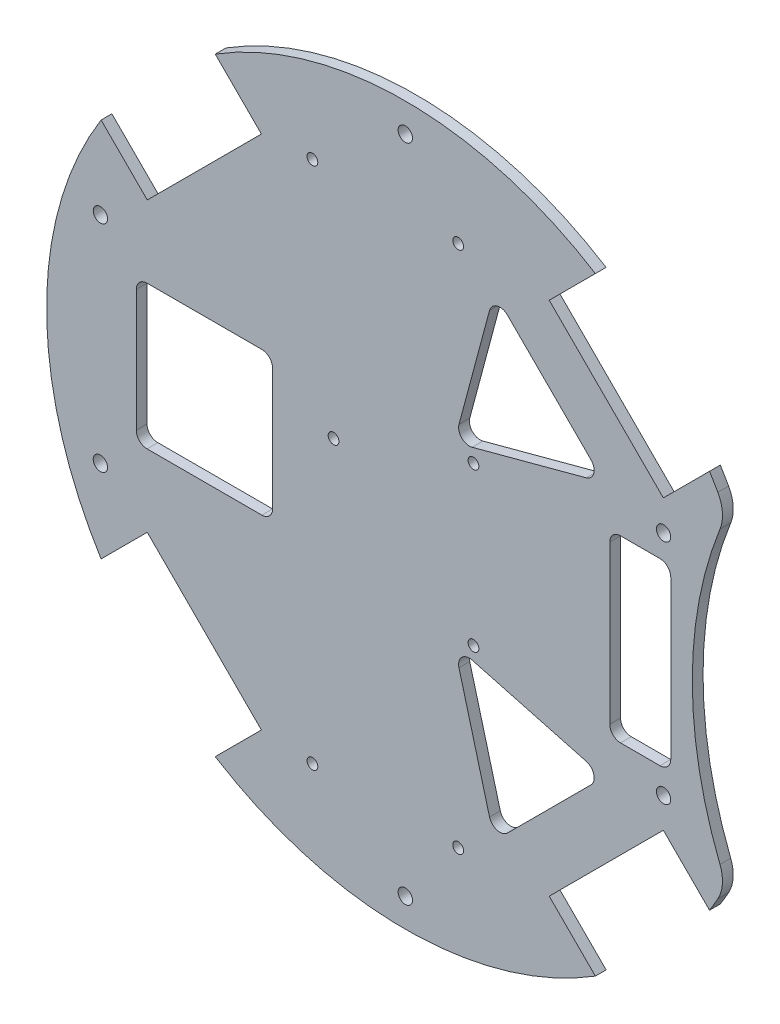
SolidWorks part; units mm, degrees
ref_plane "Alzado" through (0, 0, 0) normal (0, 0, 1) x (1, 0, 0)
ref_plane "Planta" through (0, 0, 0) normal (0, 1, 0) x (1, 0, 0)
ref_plane "Vista lateral" through (0, 0, 0) normal (1, 0, 0) x (0, 0, -1)
sketch "Croquis1" plane through (0, 0, 0) normal (0, 0, 1) x (1, 0, 0)
  circle A0 centre (0, 0) radius 100
  dimension "D1" = 200
extrude "Saliente-Extruir1" add sketch "Croquis1" along normal blind 3
sketch "Croquis3" plane through (0, 0, 3) normal (0, 0, 1) x (1, 0, 0)
  line L0 (0, 0) -> (190, 0) construction
  circle A0 centre (190, 0) radius 110
  dimension "D1" = 220
  dimension "D2" = 190
extrude "Cortar-Extruir1" cut sketch "Croquis3" against normal blind 3
fillet "Redondeo1" radius 10 2 edges at (89.4737, -44.6594, 1.5) (89.4737, 44.6594, 1.5)
sketch "Croquis7" plane through (0, 0, 3) normal (0, 0, 1) x (1, 0, 0)
  line L0 (-71.9393, -40.1195) -> (-40.1195, -71.9393)
  line L1 (-71.9393, -40.1195) -> (-89.617, -57.7972)
  line L2 (-40.1195, -71.9393) -> (-57.7972, -89.617)
  line L3 (-89.617, -57.7972) -> (-57.7972, -89.617)
  line L6 (0, -100) -> (0, 100) construction
  line L7 (-100, 0) -> (80, 0) construction
  line L8 (-40.1195, 71.9393) -> (-71.9393, 40.1195)
  line L9 (-40.1195, 71.9393) -> (-57.7972, 89.617)
  line L10 (-57.7972, 89.617) -> (-89.617, 57.7972)
  line L11 (-71.9393, 40.1195) -> (-89.617, 57.7972)
  line L12 (71.9393, 40.1195) -> (40.1195, 71.9393)
  line L13 (71.9393, 40.1195) -> (89.617, 57.7972)
  line L14 (89.617, 57.7972) -> (57.7972, 89.617)
  line L15 (40.1195, 71.9393) -> (57.7972, 89.617)
  line L16 (40.1195, -71.9393) -> (71.9393, -40.1195)
  line L17 (40.1195, -71.9393) -> (57.7972, -89.617)
  line L18 (57.7972, -89.617) -> (89.617, -57.7972)
  line L19 (71.9393, -40.1195) -> (89.617, -57.7972)
  line L20 (70.7107, -70.7107) -> (-70.7107, 70.7107) construction
  line L21 (-70.7107, -70.7107) -> (70.7107, 70.7107) construction
  arc A0 (87.1345, 49.0671) -> (87.1345, -49.0671) centre (0, 0) ccw construction
  arc A1 (87.1345, 49.0671) -> (87.1345, -49.0671) centre (0, 0) ccw construction
  arc A4 (87.7193, 40.4803) -> (87.7193, -40.4803) centre (190, 0) ccw construction
  point P24 (0, 0)
  dimension "D1" = 22.5
  dimension "D2" = 45
  dimension "D3" = 25
  dimension "D4" = 45
  dimension "D5" = 200
  dimension "D6" = 4
  dimension "D7" = 79.2376
  dimension "D8" = 22.5
  dimension "D9" = 200
  dimension "D10" = 45
  dimension "D11" = 90
  dimension "D12" = 79.2376
extrude "Cortar-Extruir3" cut sketch "Croquis7" against normal blind 10
sketch "Croquis10" plane through (0, 0, 3) normal (0, 0, 1) x (1, 0, 0)
  line L0 (80, 0) -> (-100, 0) construction
  circle A0 centre (-20, 8.5) radius 1.5
  arc A1 (-84.8075, 52.9877) -> (-84.8075, -52.9877) centre (0, 0) ccw construction
  circle A2 centre (14.74, 72.95) radius 1.5
  circle A3 centre (-25.9, 72.95) radius 1.5
  arc A4 (52.9877, 84.8075) -> (-52.9877, 84.8075) centre (0, 0) ccw construction
  arc A5 (87.7193, 40.4803) -> (87.7193, -40.4803) centre (190, 0) ccw construction
  circle A6 centre (14.74, -72.95) radius 1.5
  circle A7 centre (-25.9, -72.95) radius 1.5
  dimension "D1" = 3
  dimension "D2" = 8.5
  dimension "D3" = 20
  dimension "D4" = 3
  dimension "D5" = 3
  dimension "D6" = 40.64
  dimension "D7" = 72.95
  dimension "D8" = 25.9
  dimension "D9" = 72.95
extrude "Cortar-Extruir4" cut sketch "Croquis10" against normal through all
sketch "Croquis11" plane through (0, 0, 3) normal (0, 0, 1) x (1, 0, 0)
  line L0 (-100, 0) -> (80, 0) construction
  line L5 (0, 0) -> (0, 100) construction
  line L6 (74, 25) -> (57, 25)
  line L7 (74, 25) -> (74, -25)
  line L8 (74, -25) -> (57, -25)
  line L9 (57, 25) -> (57, -25)
  line L10 (55.4435, 35.5616) -> (24.8249, 66.1802)
  line L11 (24.8249, 66.1802) -> (13.6177, 24.3544)
  line L12 (13.6177, 24.3544) -> (55.4435, 35.5616)
  line L13 (13.6177, -24.3544) -> (55.4435, -35.5616)
  line L14 (24.8249, -66.1802) -> (13.6177, -24.3544)
  line L15 (55.4435, -35.5616) -> (24.8249, -66.1802)
  line L16 (71.9393, 40.1195) -> (84.8075, 52.9877) construction
  line L17 (-52.9877, -84.8075) -> (-40.1195, -71.9393) construction
  line L19 (-37, 20) -> (-75, 20)
  line L20 (-37, 20) -> (-37, -20)
  line L21 (-37, -20) -> (-75, -20)
  line L22 (-75, 20) -> (-75, -20)
  arc A0 (-84.8075, 52.9877) -> (-84.8075, -52.9877) centre (0, 0) ccw construction
  arc A1 (87.7193, 40.4803) -> (87.7193, -40.4803) centre (190, 0) ccw construction
  circle A2 centre (31.2953, 42.032) radius 12.5 construction
  arc A3 (52.9877, 84.8075) -> (-52.9877, 84.8075) centre (0, 0) ccw construction
  circle A4 centre (0, 92) radius 2
  circle A7 centre (0, -92) radius 2
  arc A10 (-52.9877, -84.8075) -> (52.9877, -84.8075) centre (0, 0) ccw construction
  arc A13 (-84.8075, 52.9877) -> (-84.8075, -52.9877) centre (0, 0) ccw construction
  circle A15 centre (72, 31.6949) radius 2
  circle A16 centre (72, -31.6949) radius 2
  circle A17 centre (-85, -30) radius 2
  circle A18 centre (-85, 30) radius 2
  point P45 (0, 0)
  dimension "D9" = 25
  dimension "D12" = 15
  dimension "D13" = 4
  dimension "D14" = 92
  dimension "D15" = 4
  dimension "D16" = 92
  dimension "D17" = 42.5538
  dimension "D18" = 4
  dimension "D19" = 6
  dimension "D20" = 72
  dimension "D21" = 4
  dimension "D22" = 30
  dimension "D23" = 85
  dimension "D24" = 4
  dimension "D25" = 30
  dimension "D26" = 85
  dimension "D27" = 38
  dimension "D28" = 75
  dimension "D3" = 20
  dimension "D4" = 20
  dimension "D5" = 25
  dimension "D6" = 50
  dimension "D7" = 57
  dimension "D8" = 17
  dimension "D10" = 20
  dimension "D11" = 70
extrude "Cortar-Extruir5" cut sketch "Croquis11" against normal blind 10
fillet "Redondeo2" radius 3 14 edges at (13.6177, -24.3544, 1.5) (24.8249, -66.1802, 1.5) (55.4435, -35.5616, 1.5) (74, -25, 1.5) (57, -25, 1.5) (74, 25, 1.5) (57, 25, 1.5) (55.4435, 35.5616, 1.5) (13.6177, 24.3544, 1.5) (24.8249, 66.1802, 1.5) (-75, -20, 1.5) (-37, -20, 1.5) (-75, 20, 1.5) (-37, 20, 1.5)
sketch "Croquis12" plane through (0, 0, 0) normal (0, 0, -1) x (-1, 0, 0)
  line L0 (-57, 0) -> (-2, 0) construction
  line L1 (-57, 22) -> (-57, -22) construction
  line L2 (-57, 0) -> (-19, 0) construction
  line L3 (-19, 0) -> (-19, 22) construction
  line L4 (-19, 22) -> (-19, -22) construction
  line L5 (-19, -22) -> (0, -22) construction
  line L7 (0, 22) -> (-19, 22) construction
  circle A0 centre (-19, 22) radius 1.5
  circle A2 centre (-19, -22) radius 1.5
  dimension "D4" = 3
  dimension "D7" = 3
  dimension "D1" = 22
  dimension "D2" = 38
  dimension "D3" = 22
extrude "Cortar-Extruir6" cut sketch "Croquis12" against normal through all
